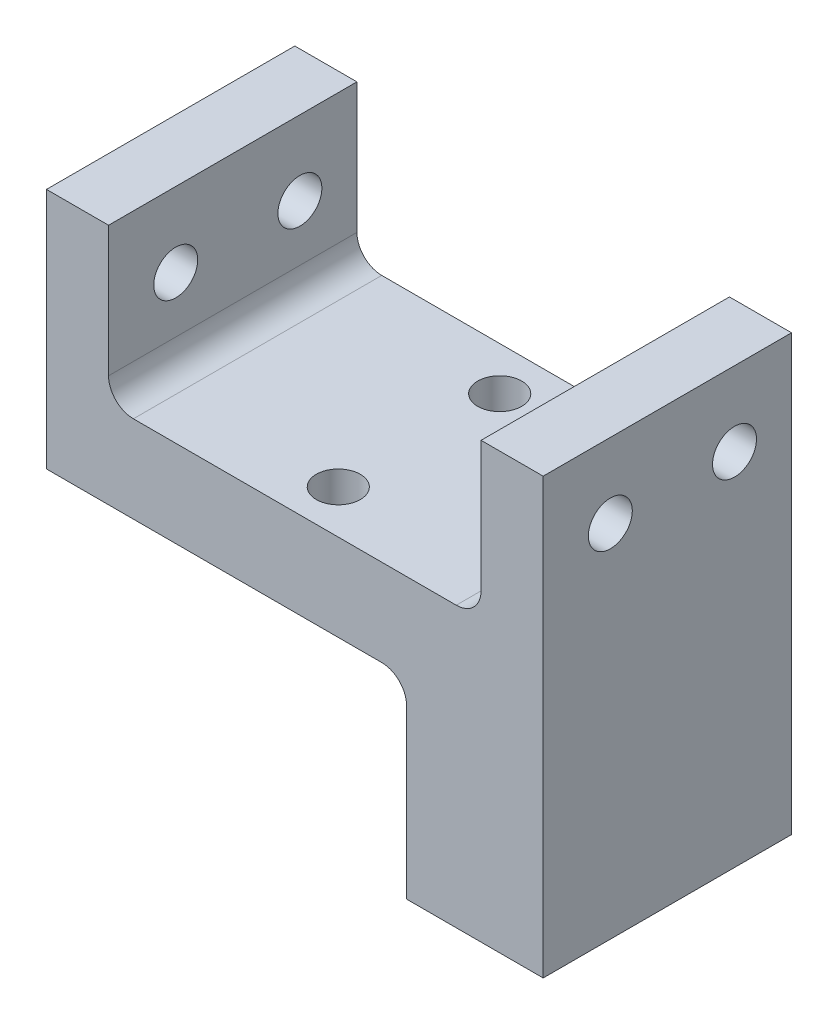
SolidWorks part; units mm, degrees
ref_plane "Front Plane" through (0, 0, 0) normal (0, 0, 1) x (1, 0, 0)
ref_plane "Top Plane" through (0, 0, 0) normal (0, 1, 0) x (1, 0, 0)
ref_plane "Right Plane" through (0, 0, 0) normal (1, 0, 0) x (0, 0, -1)
sketch "Sketch1" plane through (0, 0, 0) normal (0, 1, 0) x (1, 0, 0)
  line L1 (-25.4, -12.7) -> (25.4, -12.7)
  line L2 (-25.4, -12.7) -> (-25.4, 12.7)
  line L3 (-25.4, 12.7) -> (25.4, 12.7)
  line L4 (25.4, -12.7) -> (25.4, 12.7)
  line L5 (-25.4, -12.7) -> (25.4, 12.7) construction
  line L6 (-25.4, 12.7) -> (25.4, -12.7) construction
  point P0 (0, 0)
  dimension "D1" = 25.4
  dimension "D2" = 50.8
extrude "Boss-Extrude1" add sketch "Sketch1" along normal blind 44.45
sketch "Sketch2" plane through (0, 44.45, 0) normal (0, 1, 0) x (1, 0, 0)
  line L0 (25.4, -12.7) -> (25.4, 12.7) construction
  line L1 (-25.4, -152.4) -> (25.4, -152.4)
  line L2 (-25.4, -152.4) -> (-25.4, 0)
  line L3 (-25.4, 0) -> (25.4, 0)
  line L4 (25.4, -152.4) -> (25.4, 0)
  line L5 (-25.4, -152.4) -> (25.4, 0) construction
  line L6 (-25.4, 0) -> (25.4, -152.4) construction
  line L7 (-25.4, 12.7) -> (-25.4, -12.7) construction
  line L8 (25.4, 12.7) -> (-25.4, 12.7) construction
  point P0 (0, -76.2)
  dimension "D1" = 152.4
  dimension "D2" = 12.7
sketch "Sketch3" plane through (0, 0, -12.7) normal (0, 0, -1) x (-1, 0, 0)
  line L0 (-22.225, 5.9185) -> (22.225, 5.9185) construction
  point P2 (0, 5.9185)
  dimension "D1" = 44.45
sketch "Sketch8" plane through (0, 0, 12.7) normal (0, 0, 1) x (1, 0, 0)
  line L1 (-11.43, -19.685) -> (11.43, -19.685)
  line L2 (-11.43, -19.685) -> (-11.43, 19.685)
  line L3 (-11.43, 19.685) -> (11.43, 19.685)
  line L4 (11.43, -19.685) -> (11.43, 19.685)
  line L5 (-11.43, -19.685) -> (11.43, 19.685) construction
  line L6 (-11.43, 19.685) -> (11.43, -19.685) construction
  line L7 (-19.05, 28.575) -> (19.05, 28.575)
  line L8 (-19.05, 28.575) -> (-19.05, 60.325)
  line L9 (-19.05, 60.325) -> (19.05, 60.325)
  line L10 (19.05, 28.575) -> (19.05, 60.325)
  line L11 (-19.05, 28.575) -> (19.05, 60.325) construction
  line L12 (-19.05, 60.325) -> (19.05, 28.575) construction
  line L13 (-11.43, 19.685) -> (-32.668, 19.685)
  line L14 (-11.43, 19.685) -> (-11.43, -19.685)
  line L15 (-11.43, -19.685) -> (-32.668, -19.685)
  line L16 (-32.668, 19.685) -> (-32.668, -19.685)
  point P0 (0, 0)
  point P6 (0, 44.45)
  line M5 (-25.4, 0) -> (25.4, 0)
  line M7 (25.4, 44.45) -> (-25.4, 44.45)
  line M8 (-25.4, 44.45) -> (-25.4, 0)
  dimension "D1" = 22.86
  dimension "155" = 39.37
  dimension "D3" = 31.75
  dimension "D4" = 38.1
extrude "Cut-Extrude1" cut sketch "Sketch8" against normal through all contours L2 L13 M8 M5 | L4 L3 L2 M5 | L7 L10 L8 M7
sketch "Sketch9" plane through (25.4, 0, 0) normal (1, 0, 0) x (0, 0, -1)
  line L0 (0, 44.45) -> (-152.4, 44.45) construction
  line L1 (-5.8318, 36.83) -> (6.8682, 36.83) construction
  point P0 (6.8682, 36.83)
  point P16 (-5.8318, 36.83)
  dimension "D1" = 7.62
  dimension "D2" = 12.7
hole_wizard "#8 Clearance Hole3" positions "Sketch9" profile "Sketch10" hole size "#8" standard "ANSI Inch" end condition through all
sketch "Sketch10" plane through (25.4, 36.83, -6.8682) normal (0, 1, 0) x (0, 0, -1)
  line L0 (0, 0) -> (0, 50.8)
  line L1 (0, 50.8) -> (2.2479, 50.8)
  line L2 (2.2479, 50.8) -> (2.2479, 0)
  line L5 (2.2479, 0) -> (0, 0)
  line L11 (0, -6.35) -> (0, 107.95) construction
  dimension "Thru Hole Dia." = 4.4958
  dimension "Thru Hole Depth" = 50.8
hole_wizard "#8 Clearance Hole2" positions "Sketch13" profile "Sketch14" hole size "#8" standard "ANSI Inch" end condition through all
sketch "Sketch13" plane through (0, 28.575, 0) normal (0, 1, 0) x (1, 0, 0)
  line L0 (0, 8.255) -> (0, -8.255) construction
  point P0 (0, 8.255)
  point P2 (0, -8.255)
  point P6 (0, 0)
  dimension "D1" = 16.51
sketch "Sketch14" plane through (0, 28.575, -8.255) normal (1, 0, 0) x (0, 0, 1)
  line L0 (0, 0) -> (0, 28.575)
  line L1 (0, 28.575) -> (2.2479, 28.575)
  line L2 (2.2479, 28.575) -> (2.2479, 0)
  line L5 (2.2479, 0) -> (0, 0)
  line L11 (0, -6.35) -> (0, 107.95) construction
  dimension "Thru Hole Dia." = 4.4958
  dimension "Thru Hole Depth" = 28.575
hole_wizard "1/8 (0.18) Dowel Hole1" positions "Sketch15" profile "Sketch16" hole size "1/8" standard "ANSI Inch"
sketch "Sketch15" plane through (11.43, 0, 0) normal (-1, 0, 0) x (0, 0, 1)
  line L0 (-45.5977, 8.509) -> (-45.5977, 3.683) construction
  line L1 (-45.5977, 6.096) -> (2.9163, 6.096) construction
  point P0 (2.9163, 6.096)
sketch "Sketch16" plane through (11.43, 6.096, 2.9163) normal (0, 1, 0) x (0, 0, 1)
  line L0 (0, 0) -> (0, 8.9936)
  line L1 (0, 8.9936) -> (2.286, 7.62)
  line L2 (2.286, 7.62) -> (2.286, 0)
  line L5 (2.286, 0) -> (0, 0)
  line L10 (0, 8.9936) -> (-2.286, 7.62) construction
  line L11 (0, -6.35) -> (0, 107.95) construction
  dimension "Hole Dia." = 4.572
  dimension "Hole Depth" = 7.62
  dimension "Drill Angle" = 118
fillet "Fillet1" radius 2.54 3 edges at (11.43, 19.685, 0) (-19.05, 28.575, 0) (19.05, 28.575, 0)
sketch "Sketch17" plane through (0, 0, -12.7) normal (0, 0, 1) x (1, 0, 0)
  line L0 (-22.225, 27.5085) -> (22.225, 27.5085) construction
  line L1 (22.225, 5.9185) -> (-22.225, 5.9185) construction
  circle A0 centre (-22.225, 27.5085) radius 1.27
  circle A1 centre (22.225, 27.5085) radius 1.27
  point P2 (0, 27.5085)
  dimension "D3" = 2.54
  dimension "D1" = 44.45
  dimension "D2" = 21.59
extrude "Cut-Extrude3" cut sketch "Sketch17" along normal blind 12.7
